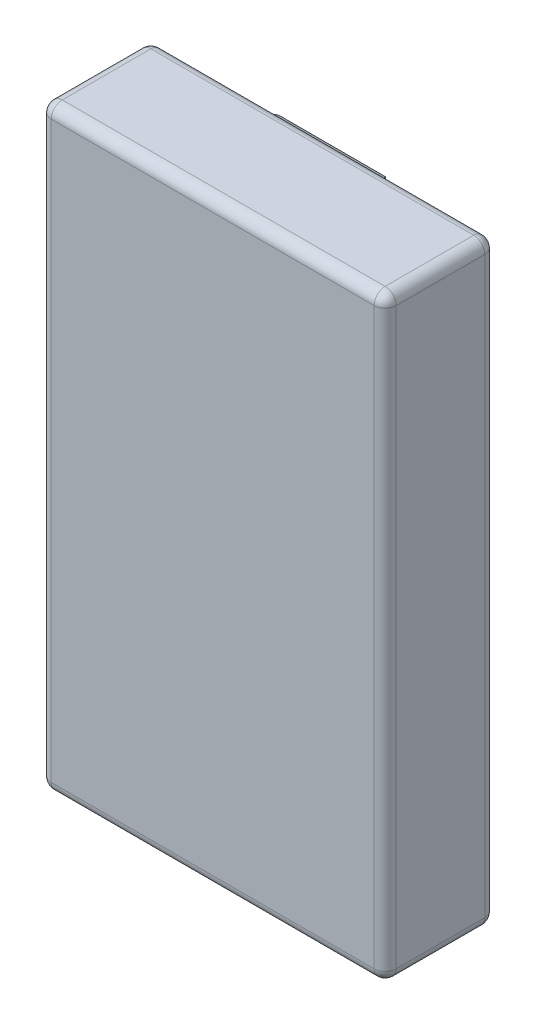
SolidWorks part; units mm, degrees
ref_plane "前基準面" through (0, 0, 0) normal (0, 0, 1) x (1, 0, 0)
ref_plane "上基準面" through (0, 0, 0) normal (0, 1, 0) x (1, 0, 0)
ref_plane "右基準面" through (0, 0, 0) normal (1, 0, 0) x (0, 0, -1)
sketch "草圖1" plane through (0, 0, 0) normal (0, 0, 1) x (1, 0, 0)
  line L0 (0, 0) -> (0, -87.2076) construction
  line L2 (-15.5864, -16.6557) -> (15.5864, -16.6557)
  line L3 (-15.5864, -16.6557) -> (-15.5864, -70.5519)
  line L4 (-15.5864, -70.5519) -> (15.5864, -70.5519)
  line L5 (15.5864, -16.6557) -> (15.5864, -70.5519)
  line L6 (-15.5864, -16.6557) -> (15.5864, -70.5519) construction
  line L7 (-15.5864, -70.5519) -> (15.5864, -16.6557) construction
  point P3 (0, -43.6038)
extrude "填料-伸長1" add sketch "草圖1" along normal blind 10
sketch "草圖2" plane through (0, 0, 0) normal (0, 0, 1) x (1, 0, 0)
  line L4 (5, -17.6789) -> (-5, -17.6789)
  line L5 (5, -17.6789) -> (5, -22.6789)
  line L6 (5, -22.6789) -> (-5, -22.6789)
  line L7 (-5, -17.6789) -> (-5, -22.6789)
  line L8 (5, -17.6789) -> (-5, -22.6789) construction
  line L9 (5, -22.6789) -> (-5, -17.6789) construction
  point P6 (0, -20.1789)
extrude "填料-伸長3" add sketch "草圖2" against normal blind 1.2
fillet "圓角1" radius 1 4 edges at (-5, -20.1789, -1.2) (5, -20.1789, -1.2) (0, -17.6789, -1.2) (0, -22.6789, -1.2)
fillet "圓角2" radius 1 12 edges at (15.5864, -70.5519, 5) (15.5864, -43.6038, 10) (15.5864, -16.6557, 5) (15.5864, -43.6038, 0) (0, -70.5519, 10) (0, -70.5519, 0) (0, -16.6557, 10) (0, -16.6557, 0) (-15.5864, -16.6557, 5) (-15.5864, -70.5519, 5) (-15.5864, -43.6038, 10) (-15.5864, -43.6038, 0)
